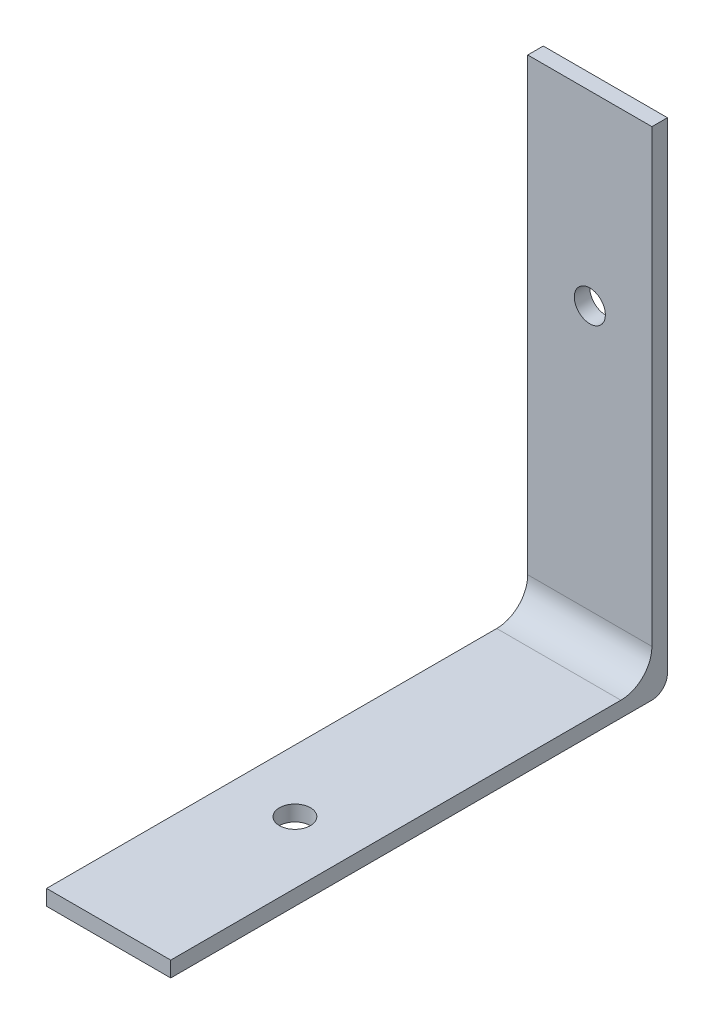
SolidWorks part; units mm, degrees
ref_plane "Front" through (0, 0, 0) normal (0, 0, 1) x (1, 0, 0)
ref_plane "Top" through (0, 0, 0) normal (0, 1, 0) x (1, 0, 0)
ref_plane "Right" through (0, 0, 0) normal (1, 0, 0) x (0, 0, -1)
sketch "Sketch1" plane through (0, 0, 0) normal (1, 0, 0) x (0, 0, -1)
  line L0 (0, 0) -> (49.2125, 0)
  line L1 (50.8, 1.5875) -> (50.8, 50.8)
  line L2 (50.8, 50.8) -> (49.2125, 50.8)
  line L3 (49.2125, 50.8) -> (49.2125, 4.7625)
  line L4 (46.0375, 1.5875) -> (0, 1.5875)
  line L5 (0, 1.5875) -> (0, 0)
  arc A0 (49.2125, 0) -> (50.8, 1.5875) centre (49.2125, 1.5875) ccw
  arc A1 (49.2125, 4.7625) -> (46.0375, 1.5875) centre (46.0375, 4.7625) cw
  dimension "D3" = 1.5875
  dimension "D4" = 3.175
  dimension "D1" = 50.8
  dimension "D2" = 50.8
  dimension "D5" = 1.5875
extrude "Boss-Extrude1" add sketch "Sketch1" along normal blind 12.7
sketch "Sketch2" plane through (0, 0, -49.2125) normal (0, 0, 1) x (1, 0, 0)
  line L0 (12.7, 50.8) -> (0, 50.8) construction
  line L1 (0, 50.8) -> (0, 4.7625) construction
  circle A0 centre (6.35, 31.75) radius 1.5875
  dimension "D1" = 3.175
  dimension "D3" = 6.35
  dimension "D2" = 19.05
sketch "Sketch3" plane through (0, 1.5875, 0) normal (0, 1, 0) x (1, 0, 0)
  line L1 (12.7, 0) -> (0, 0) construction
  line L2 (12.7, 46.0375) -> (12.7, 0) construction
  circle A0 centre (6.35, 19.05) radius 1.5875
  dimension "D1" = 19.05
  dimension "D2" = 3.175
  dimension "D3" = 6.35
extrude "Cut-Extrude1" cut sketch "Sketch2" against normal blind 17.526
extrude "Cut-Extrude2" cut sketch "Sketch3" against normal blind 17.526
